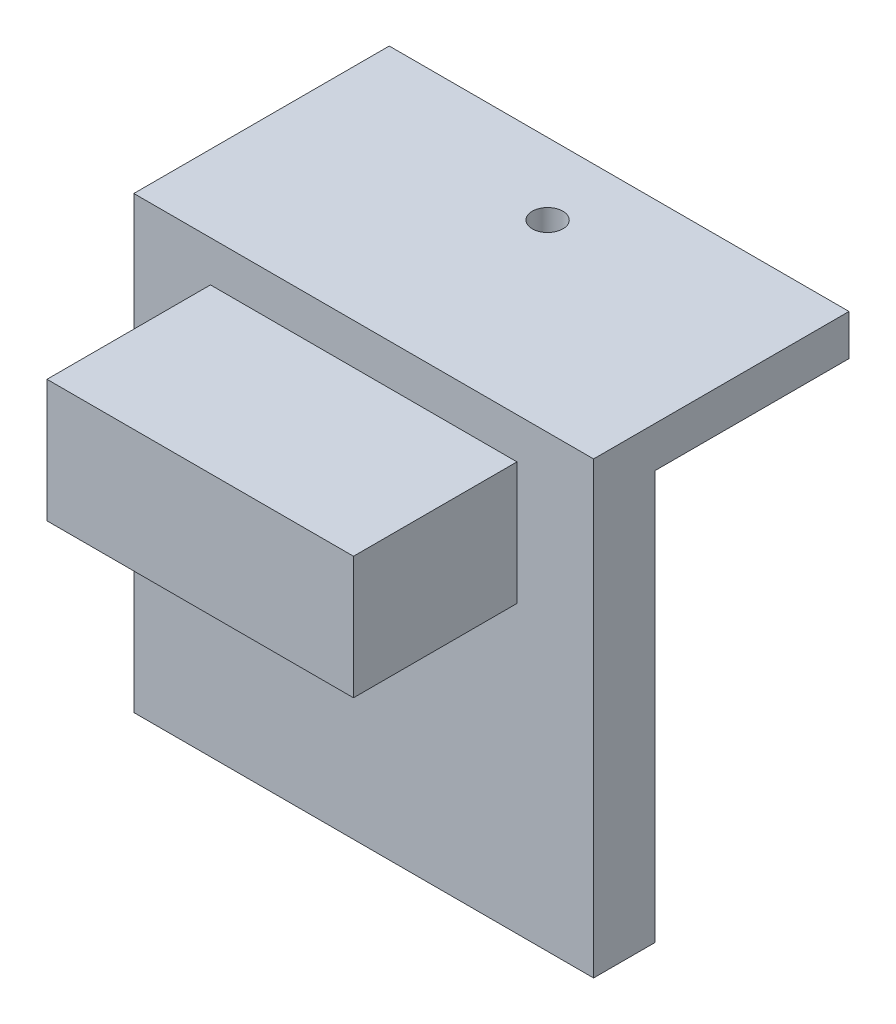
SolidWorks part; units mm, degrees
material "Perspex (TM) GS Acrylic Cast Sheet"
ref_plane "Front Plane" through (0, 0, 0) normal (0, 0, 1) x (1, 0, 0)
ref_plane "Top Plane" through (0, 0, 0) normal (0, 1, 0) x (1, 0, 0)
ref_plane "Right Plane" through (0, 0, 0) normal (1, 0, 0) x (0, 0, -1)
sketch "Sketch1" plane through (0, 0, 0) normal (0, 0, 1) x (1, 0, 0)
  line L1 (-22.5, 20) -> (22.5, 20)
  line L2 (-22.5, 20) -> (-22.5, -20)
  line L3 (-22.5, -20) -> (22.5, -20)
  line L4 (22.5, 20) -> (22.5, -20)
  line L5 (-22.5, 20) -> (22.5, -20) construction
  line L6 (-22.5, -20) -> (22.5, 20) construction
  point P0 (0, 0)
  dimension "D1" = 40
  dimension "D2" = 45
extrude "Boss-Extrude1" add sketch "Sketch1" along normal blind 6
sketch "Sketch2" plane through (0, 0, 6) normal (0, 0, 1) x (1, 0, 0)
  line L0 (22.5, 20) -> (-22.5, 20) construction
  line L1 (-15, 20) -> (15, 20)
  line L2 (-15, 20) -> (-15, 8)
  line L3 (-15, 8) -> (15, 8)
  line L4 (15, 20) -> (15, 8)
  line L5 (0, -3.3) -> (0, 3.3) construction
  dimension "D1" = 12
  dimension "D2" = 30
  dimension "D3" = 15
extrude "Boss-Extrude2" add sketch "Sketch2" along normal blind 16
sketch "Sketch3" plane through (0, 20, 0) normal (0, 1, 0) x (1, 0, 0)
  line L0 (0, -12.1) -> (0, 12.1) construction
  line L1 (-22.5, -6) -> (22.5, -6)
  line L2 (-22.5, -6) -> (-22.5, 19)
  line L3 (-22.5, 19) -> (22.5, 19)
  line L4 (22.5, -6) -> (22.5, 19)
  circle A0 centre (0, 12) radius 1.5
  dimension "D2" = 3
  dimension "D3" = 7
  dimension "D1" = 25
extrude "Boss-Extrude3" add sketch "Sketch3" along normal blind 4
